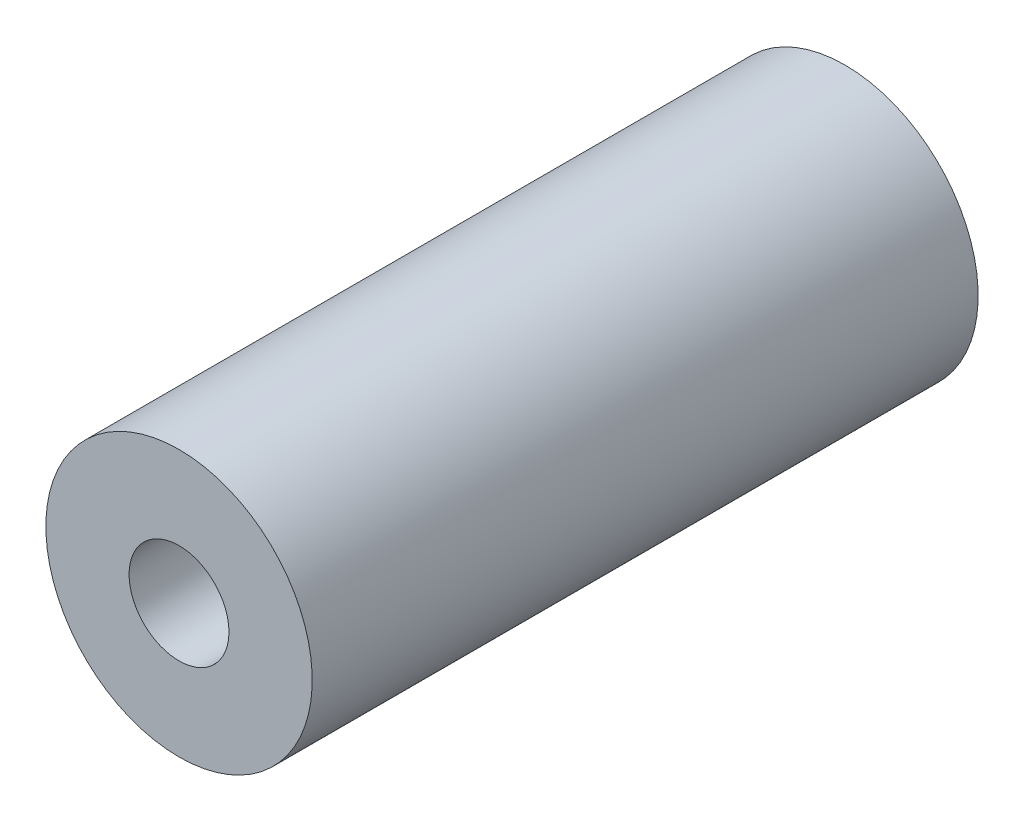
SolidWorks part; units mm, degrees
ref_plane "Plan de face" through (0, 0, 0) normal (0, 0, 1) x (1, 0, 0)
ref_plane "Plan de dessus" through (0, 0, 0) normal (0, 1, 0) x (1, 0, 0)
ref_plane "Plan de droite" through (0, 0, 0) normal (1, 0, 0) x (0, 0, -1)
sketch "Esquisse1" plane through (0, 0, 0) normal (1, 0, 0) x (0, 0, -1)
  line L0 (0, 0) -> (0, -6)
  line L6 (30, -6) -> (30, 0)
  line L7 (30, 0) -> (0, 0)
  line L8 (0, -6) -> (30, -6)
  dimension "D1" = 30
  dimension "D4" = 6
revolve "Révolution1" add sketch "Esquisse1" angle 360 about L7
sketch "Esquisse2" plane through (0, 0, 0) normal (0, 0, 1) x (1, 0, 0)
  line L0 (0, 0) -> (0, 1.5) construction
  line L1 (0, 0) -> (0, -2.25) construction
  line L2 (0, 1.5) -> (1.6771, 1.5)
  line L3 (0, 1.5) -> (-1.6771, 1.5)
  circle A0 centre (0, 0) radius 2.25
  dimension "D1" = 4.5
  dimension "D2" = 1.5
sketch "Esquisse3" plane through (0, 0, -30) normal (0, 0, -1) x (-1, 0, 0)
  line L0 (-3.62, 2.6731) -> (3.62, 2.6731)
  circle A0 centre (0, 0) radius 4.5
  dimension "D1" = 9
extrude "Enlèv. mat.-Extru.4" cut sketch "Esquisse2" against normal blind 5 contours L2 A0 L3
sketch "Esquisse5" plane through (0, 0, 0) normal (0, 0, 1) x (1, 0, 0)
  line L0 (-1.6771, 1.5) -> (1.6771, 1.5)
  circle A0 centre (0, 0) radius 2.25
  arc A1 (-1.6771, 1.5) -> (1.6771, 1.5) centre (0, 0) ccw
  line M3 (1.6771, 1.5) -> (-1.6771, 1.5)
  dimension "D1" = 4.5
extrude "Enlèv. mat.-Extru.5" cut sketch "Esquisse5" against normal blind 18 contours A0 M3
extrude "Enlèv. mat.-Extru.6" cut sketch "Esquisse3" against normal blind 15 contours L0 A0
